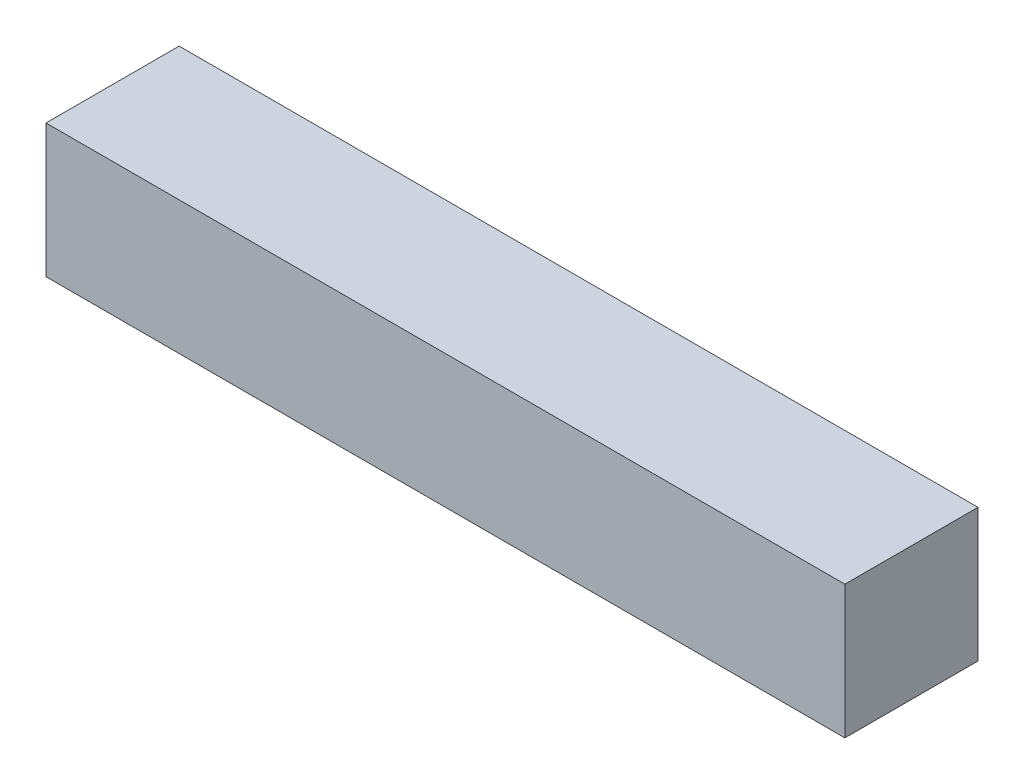
SolidWorks part; units mm, degrees
ref_plane "Plan de face" through (0, 0, 0) normal (0, 0, 1) x (1, 0, 0)
ref_plane "Plan de dessus" through (0, 0, 0) normal (0, 1, 0) x (1, 0, 0)
ref_plane "Plan de droite" through (0, 0, 0) normal (1, 0, 0) x (0, 0, -1)
sketch "Esquisse1" plane through (0, 0, 0) normal (0, 0, 1) x (1, 0, 0)
  line L1 (-9, -1.5) -> (9, -1.5)
  line L2 (-9, -1.5) -> (-9, 1.5)
  line L3 (-9, 1.5) -> (9, 1.5)
  line L4 (9, -1.5) -> (9, 1.5)
  line L5 (-9, -1.5) -> (9, 1.5) construction
  line L6 (-9, 1.5) -> (9, -1.5) construction
  point P0 (0, 0)
  dimension "D1" = 18
  dimension "D2" = 3
extrude "Boss.-Extru.1" add sketch "Esquisse1" along normal blind 3
